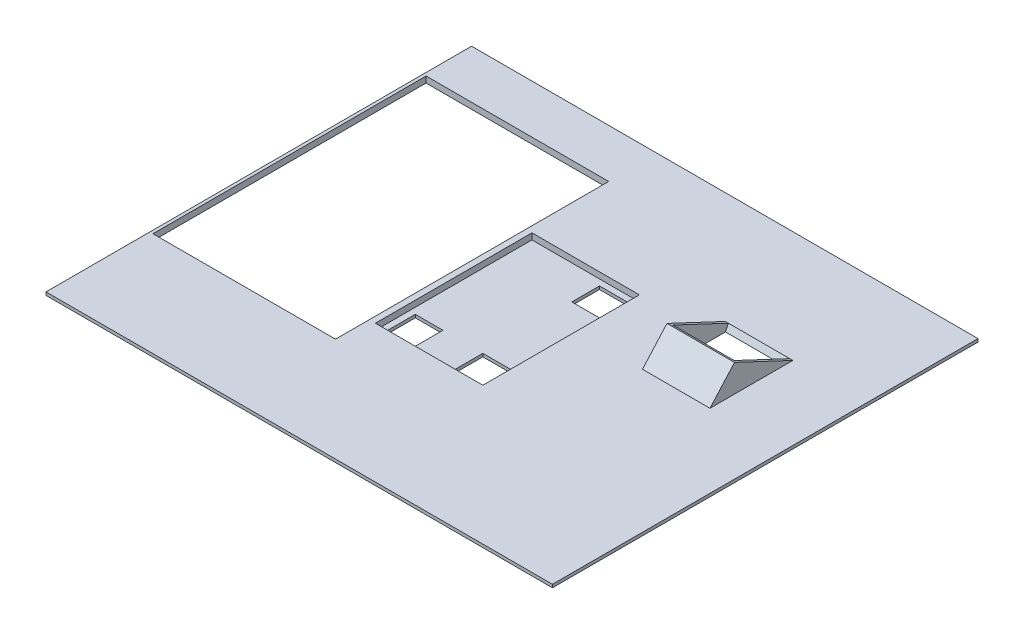
SolidWorks part; units mm, degrees
ref_plane "Front Plane" through (0, 0, 0) normal (0, 0, 1) x (1, 0, 0)
ref_plane "Top Plane" through (0, 0, 0) normal (0, 1, 0) x (1, 0, 0)
ref_plane "Right Plane" through (0, 0, 0) normal (1, 0, 0) x (0, 0, -1)
sketch "Sketch1" plane through (0, 0, 0) normal (0, 1, 0) x (1, 0, 0)
  line L1 (0, 0) -> (167, 0)
  line L2 (0, 0) -> (0, 140.66)
  line L3 (0, 140.66) -> (167, 140.66)
  line L4 (167, 0) -> (167, 140.66)
  dimension "D1" = 140.66
  dimension "D2" = 167
extrude "Boss-Extrude1" add sketch "Sketch1" against normal blind 2 draft 45
sketch "Sketch2" plane through (0, -2, 0) normal (0, -1, 0) x (1, 0, 0)
  line L4 (167, -140.66) -> (0, -140.66) construction
  line L5 (167, 0) -> (167, -140.66) construction
  line L6 (0, 0) -> (167, 0) construction
  line L7 (0, -140.66) -> (0, 0) construction
  line L8 (1, -1) -> (1, -139.66)
  line L9 (1, -139.66) -> (166, -139.66)
  line L10 (166, -139.66) -> (166, -1)
  line L11 (166, -1) -> (1, -1)
  line L12 (1, -1) -> (1, -139.66)
  line L13 (1, -139.66) -> (166, -139.66)
  line L14 (166, -139.66) -> (166, -1)
  line L15 (166, -1) -> (1, -1)
  line L16 (167, -140.66) -> (0, -140.66)
  line L17 (167, 0) -> (167, -140.66)
  line L18 (0, 0) -> (167, 0)
  line L19 (0, -140.66) -> (0, 0)
  dimension "D1" = 1
extrude "Cut-Extrude1" cut sketch "Sketch2" against normal up to next
sketch "Sketch3" plane through (0, 0, 0) normal (1, 0, 0) x (0, 0, -1)
  line L0 (76.33, 0) -> (84.33, 8.9443)
  line L1 (1, 0) -> (139.66, 0) construction
  line L2 (84.33, 8.9443) -> (103.33, 0)
  line L4 (76.33, 0) -> (103.33, 0)
  line L5 (70.33, 0) -> (70.33, 50000) construction
  line L6 (115.83, 0) -> (115.83, 50000)
  point P5 (107.6712, 0)
  point P9 (70.33, 0)
  dimension "D1" = 21
  dimension "D2" = 12
  dimension "D3" = 27
  dimension "D4" = 12.5
  dimension "D5" = 45.5
extrude "Boss-Extrude2" add sketch "Sketch3" along normal blind 22 from offset 120
sketch "Sketch4" plane through (0, 39.8186, -18.7447) normal (0, 0.9048, -0.4259) x (1, 0, 0)
  line L0 (142, 93.489) -> (120, 93.489) construction
  line L1 (141, 93.489) -> (121, 93.489)
  line L10 (121, 92.489) -> (121, 73.489)
  line L11 (121, 73.489) -> (141, 73.489)
  line L12 (141, 73.489) -> (141, 92.489)
  line L13 (141, 92.489) -> (121, 92.489)
  line L14 (121, 93.489) -> (121, 73.489)
  line L15 (121, 73.489) -> (141, 73.489)
  line L16 (141, 73.489) -> (141, 93.489)
  dimension "D1" = 1
extrude "Cut-Extrude2" cut sketch "Sketch4" against normal up to next
sketch "Sketch5" plane through (0, 0, 0) normal (0, 1, 0) x (1, 0, 0)
  line L0 (166, 1) -> (166, 139.66) construction
  line L1 (87.5, 94.83) -> (96.5, 94.83)
  line L2 (87.5, 94.83) -> (87.5, 85.83)
  line L3 (87.5, 85.83) -> (96.5, 85.83)
  line L4 (96.5, 94.83) -> (96.5, 85.83)
  line L6 (87.5, 47.83) -> (96.5, 47.83)
  line L7 (87.5, 47.83) -> (87.5, 56.83)
  line L8 (87.5, 56.83) -> (96.5, 56.83)
  line L9 (96.5, 47.83) -> (96.5, 56.83)
  line L10 (65.5, 56.83) -> (74.5, 56.83)
  line L11 (65.5, 56.83) -> (65.5, 47.83)
  line L12 (65.5, 47.83) -> (74.5, 47.83)
  line L13 (74.5, 56.83) -> (74.5, 47.83)
  line L15 (1, 70.33) -> (-49999, 70.33) construction
  line L16 (1, 139.66) -> (1, 1) construction
  line L17 (1, 115.83) -> (-49999, 115.83) construction
  line L18 (1, 24.83) -> (-49999, 24.83) construction
  point P20 (1, 70.33)
  dimension "D1" = 9
  dimension "D3" = 78.5
  dimension "D4" = 70
  dimension "D5" = 78.5
  dimension "D6" = 32
  dimension "D7" = 9
  dimension "D10" = 100.5
  dimension "D11" = 9
  dimension "D12" = 9
  dimension "D13" = 32
  dimension "D8" = 45.5
  dimension "D9" = 45.5
extrude "Cut-Extrude3" cut sketch "Sketch5" against normal through all both and the other way through all
sketch "Sketch6" plane through (0, 0, 0) normal (0, 1, 0) x (1, 0, 0)
  line L0 (1, 139.66) -> (1, 1) construction
  line L1 (2, 123.83) -> (61.5, 123.83)
  line L2 (2, 123.83) -> (2, 34.83)
  line L3 (2, 34.83) -> (61.5, 34.83)
  line L4 (61.5, 123.83) -> (61.5, 34.83)
  line L5 (200001, 24.83) -> (-249999, 24.83) construction
  dimension "D1" = 59.5
  dimension "D2" = 1
  dimension "D3" = 10
  dimension "D4" = 89
extrude "Cut-Extrude4" cut sketch "Sketch6" against normal up to next
sketch "Sketch7" plane through (0, 0, 0) normal (0, 1, 0) x (1, 0, 0)
  line L0 (63.5, 96.83) -> (63.5, 45.83)
  line L3 (98.5, 96.83) -> (98.5, 45.83)
  line L4 (63.5, 96.83) -> (98.5, 96.83)
  line L5 (63.5, 45.83) -> (98.5, 45.83)
  line L6 (61.5, 34.83) -> (61.5, 123.83) construction
  line L8 (96.5, 85.83) -> (96.5, 94.83) construction
  line L9 (96.5, 94.83) -> (87.5, 94.83) construction
  line L10 (87.5, 47.83) -> (96.5, 47.83) construction
  dimension "D1" = 2
  dimension "D2" = 2
  dimension "D3" = 2
  dimension "D4" = 2
extrude "Cut-Extrude5" cut sketch "Sketch7" against normal blind 2
sketch "Sketch11" plane through (0, 0, 0) normal (0, 1, 0) x (1, 0, 0)
  line L14 (61.5, 43.83) -> (100.5, 43.83)
  line L15 (100.5, 43.83) -> (100.5, 98.83)
  line L16 (61.5, 98.83) -> (61.5, 43.83)
  line L17 (100.5, 98.83) -> (61.5, 98.83)
  line L18 (61.5, 43.83) -> (100.5, 43.83)
  line L19 (100.5, 43.83) -> (100.5, 98.83)
  line L20 (61.5, 98.83) -> (61.5, 43.83)
  line L21 (100.5, 98.83) -> (61.5, 98.83)
  dimension "D1" = 2
extrude "Boss-Extrude4" add sketch "Sketch11" against normal blind 1 from surface at -2 starting at face at (81, -2, -71.33)
sketch "Sketch12" plane through (0, 0, 0) normal (0, 1, 0) x (1, 0, 0)
  line L0 (87.5, 47.83) -> (96.5, 47.83) construction
  line L1 (96.5, 47.83) -> (96.5, 56.83) construction
  line L2 (87.5, 56.83) -> (96.5, 56.83) construction
  line L3 (87.5, 47.83) -> (87.5, 56.83) construction
  line L4 (74.5, 56.83) -> (74.5, 47.83) construction
  line L5 (65.5, 47.83) -> (74.5, 47.83) construction
  line L6 (65.5, 56.83) -> (65.5, 47.83) construction
  line L7 (65.5, 56.83) -> (74.5, 56.83) construction
  line L8 (96.5, 94.83) -> (96.5, 85.83) construction
  line L9 (87.5, 85.83) -> (96.5, 85.83) construction
  line L10 (87.5, 94.83) -> (96.5, 94.83) construction
  line L11 (87.5, 94.83) -> (87.5, 85.83) construction
  line L12 (87.5, 47.83) -> (96.5, 47.83)
  line L13 (96.5, 47.83) -> (96.5, 56.83)
  line L14 (87.5, 56.83) -> (96.5, 56.83)
  line L15 (87.5, 47.83) -> (87.5, 56.83)
  line L16 (74.5, 56.83) -> (74.5, 47.83)
  line L17 (65.5, 47.83) -> (74.5, 47.83)
  line L18 (65.5, 56.83) -> (65.5, 47.83)
  line L19 (65.5, 56.83) -> (74.5, 56.83)
  line L20 (96.5, 94.83) -> (96.5, 85.83)
  line L21 (87.5, 85.83) -> (96.5, 85.83)
  line L22 (87.5, 94.83) -> (96.5, 94.83)
  line L23 (87.5, 94.83) -> (87.5, 85.83)
extrude "Cut-Extrude6" cut sketch "Sketch12" against normal through all both and the other way through all
